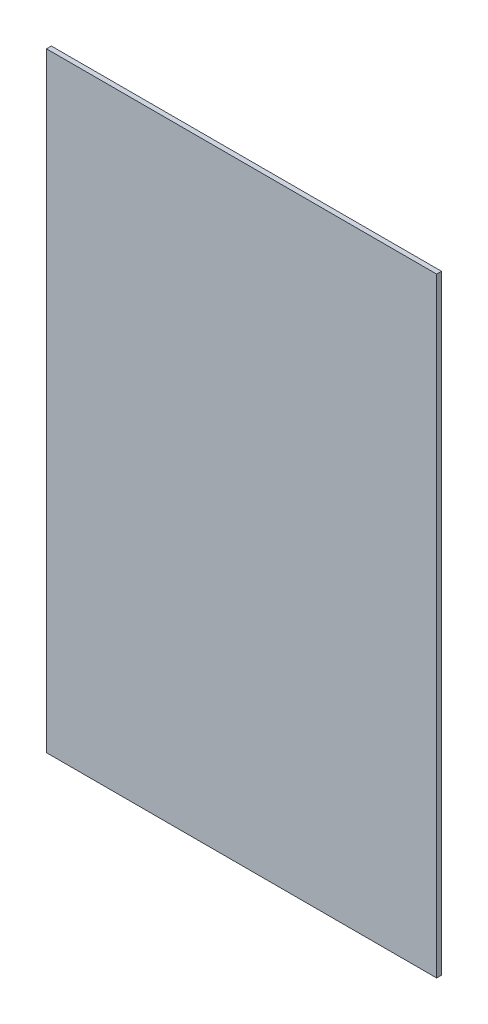
SolidWorks part; units mm, degrees
ref_plane "前视基准面" through (0, 0, 0) normal (0, 0, 1) x (1, 0, 0)
ref_plane "上视基准面" through (0, 0, 0) normal (0, 1, 0) x (1, 0, 0)
ref_plane "右视基准面" through (0, 0, 0) normal (1, 0, 0) x (0, 0, -1)
sketch "草图1" plane through (0, 0, 0) normal (0, 0, 1) x (1, 0, 0)
  line L1 (-22.9235, 88.4354) -> (57.0765, 88.4354)
  line L2 (-22.9235, 88.4354) -> (-22.9235, -36.5646)
  line L3 (-22.9235, -36.5646) -> (57.0765, -36.5646)
  line L4 (57.0765, 88.4354) -> (57.0765, -36.5646)
  dimension "D1" = 80
  dimension "D2" = 125
extrude "凸台-拉伸1" add sketch "草图1" along normal blind 1 contours L1 L4 L3 L2
